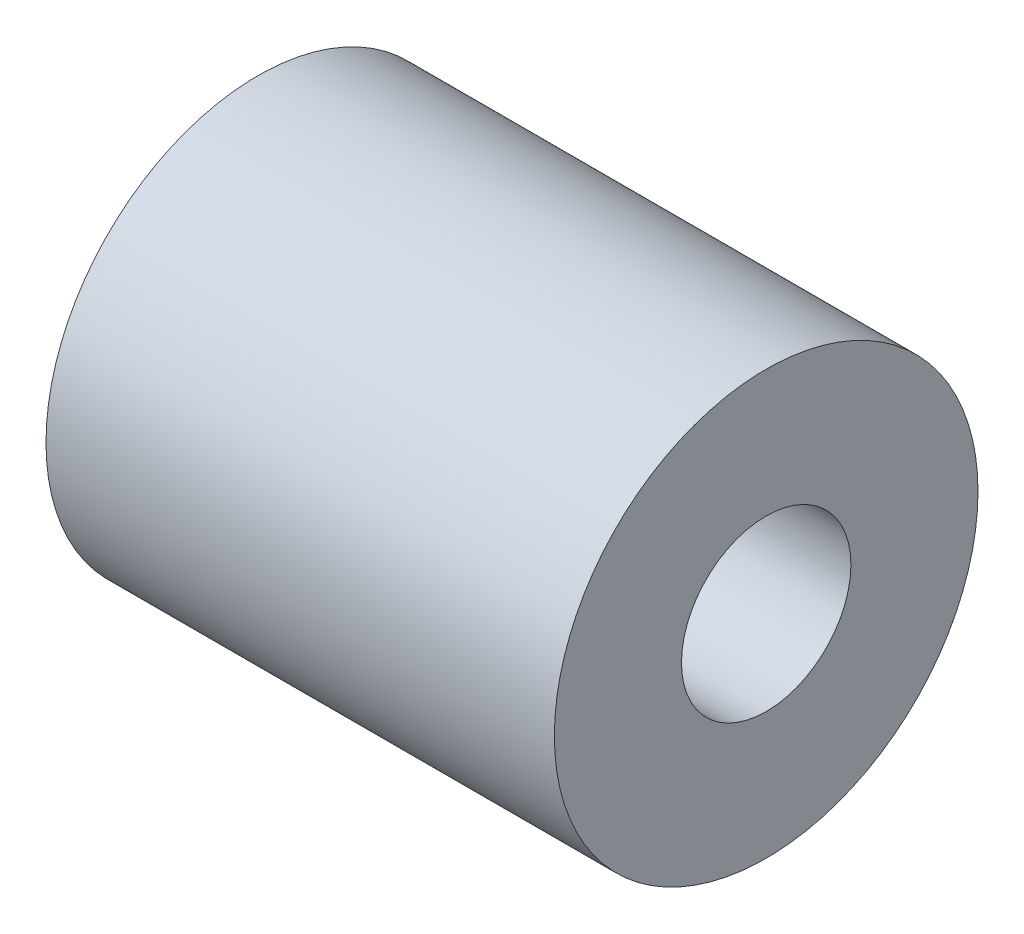
SolidWorks part; units mm, degrees
material "6063-T5"
ref_plane "Front Plane" through (0, 0, 0) normal (0, 0, 1) x (1, 0, 0)
ref_plane "Top Plane" through (0, 0, 0) normal (0, 1, 0) x (1, 0, 0)
ref_plane "Right Plane" through (0, 0, 0) normal (1, 0, 0) x (0, 0, -1)
sketch "Sketch1" plane through (0, 0, 0) normal (0, 0, 1) x (1, 0, 0)
  line L0 (0, 10) -> (24, 10)
  line L1 (24, 10) -> (24, 4)
  line L2 (24, 4) -> (12, 4)
  line L3 (12, 4) -> (12, 2.5)
  line L4 (12, 2.5) -> (0, 2.5)
  line L5 (0, 2.5) -> (0, 10)
  line L6 (0, 0) -> (27.0833, 0) construction
  point P9 (13.7742, 4)
  point P10 (11.3442, 2.5)
  dimension "D1" = 2.5
  dimension "D2" = 4
  dimension "D3" = 24
  dimension "D5" = 10
revolve "Revolve1" add sketch "Sketch1" angle 360 about L6
equation "\"D1\"= \"1st Shaft Depth\""
